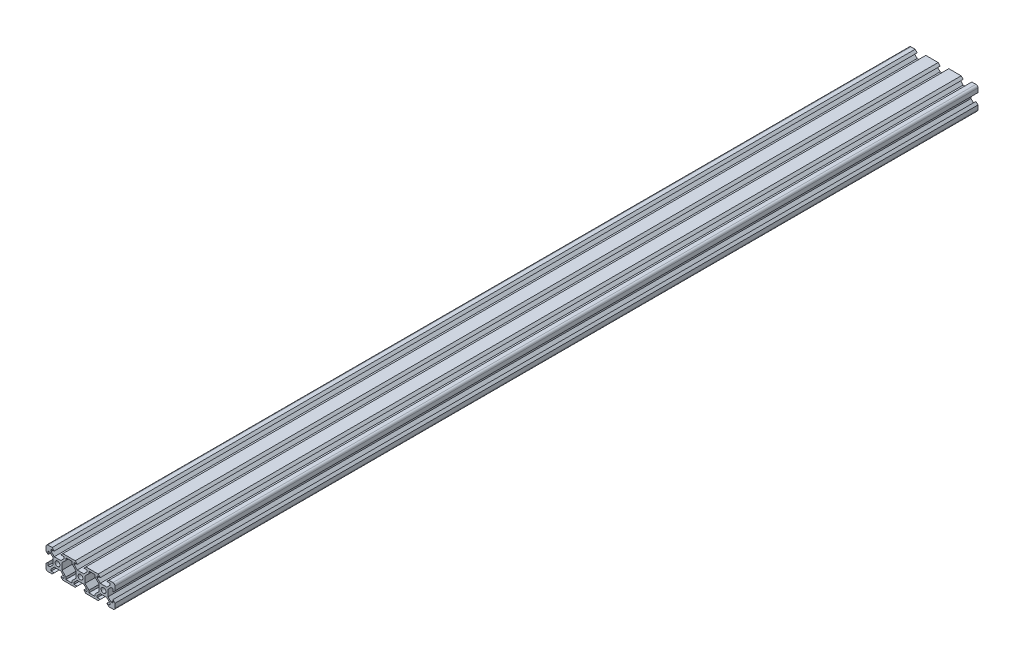
SolidWorks part; units mm, degrees
ref_plane "Front Plane" through (0, 0, 0) normal (0, 0, 1) x (1, 0, 0)
ref_plane "Top Plane" through (0, 0, 0) normal (0, 1, 0) x (1, 0, 0)
ref_plane "Right Plane" through (0, 0, 0) normal (1, 0, 0) x (0, 0, -1)
ref_plane "Plane1" through (0, 0, 10) normal (0, 0, 1) x (1, 0, 0)
sketch "Sketch1" plane through (0, 0, 10) normal (0, 0, 1) x (1, 0, 0)
  line L0 (-13.9007, 2.84) -> (-13.9007, -2.84)
  line L1 (-13.9007, -2.84) -> (-17.3007, -6.24)
  line L2 (-17.3007, -6.24) -> (-17.3007, -8.2)
  line L3 (-17.3007, -8.2) -> (-22.6993, -8.2)
  line L4 (-22.6993, -8.2) -> (-22.6993, -6.24)
  line L5 (-22.6993, -6.24) -> (-26.0993, -2.84)
  line L6 (-26.0993, -2.84) -> (-26.0993, 2.84)
  line L7 (-26.0993, 2.84) -> (-22.6993, 6.24)
  line L8 (-22.6993, 6.24) -> (-22.6993, 8.2)
  line L9 (-22.6993, 8.2) -> (-17.3007, 8.2)
  line L10 (-17.3007, 8.2) -> (-17.3007, 6.24)
  line L11 (-17.3007, 6.24) -> (-13.9007, 2.84)
  line L12 (-6.0993, -2.84) -> (-6.0993, 2.84)
  line L13 (-6.0993, 2.84) -> (-2.6993, 6.24)
  line L14 (-2.6993, 6.24) -> (-2.6993, 8.2)
  line L15 (-2.6993, 8.2) -> (2.6993, 8.2)
  line L16 (2.6993, 8.2) -> (2.6993, 6.24)
  line L17 (2.6993, 6.24) -> (6.0993, 2.84)
  line L18 (6.0993, 2.84) -> (6.0993, -2.84)
  line L19 (6.0993, -2.84) -> (2.6993, -6.24)
  line L20 (2.6993, -6.24) -> (2.6993, -8.2)
  line L21 (2.6993, -8.2) -> (-2.6993, -8.2)
  line L22 (-2.6993, -8.2) -> (-2.6993, -6.24)
  line L23 (-2.6993, -6.24) -> (-6.0993, -2.84)
  line L24 (-12.84, -8.2) -> (-15.4993, -8.2)
  line L25 (-15.4993, -8.2) -> (-15.4993, -6.56)
  line L26 (-15.4993, -6.56) -> (-12.84, -3.9007)
  line L27 (-12.84, -3.9007) -> (-7.16, -3.9007)
  line L28 (-7.16, -3.9007) -> (-4.5007, -6.56)
  line L29 (-4.5007, -6.56) -> (-4.5007, -8.2)
  line L30 (-4.5007, -8.2) -> (-7.16, -8.2)
  line L31 (-7.16, -8.2) -> (-5.36, -10)
  line L32 (-5.36, -10) -> (5.36, -10)
  line L33 (5.36, -10) -> (7.16, -8.2)
  line L34 (7.16, -8.2) -> (4.5007, -8.2)
  line L35 (4.5007, -8.2) -> (4.5007, -6.56)
  line L36 (4.5007, -6.56) -> (7.16, -3.9007)
  line L37 (7.16, -3.9007) -> (12.84, -3.9007)
  line L38 (12.84, -3.9007) -> (15.4993, -6.56)
  line L39 (15.4993, -6.56) -> (15.4993, -8.2)
  line L40 (15.4993, -8.2) -> (12.84, -8.2)
  line L41 (12.84, -8.2) -> (14.64, -10)
  line L42 (14.64, -10) -> (18.2, -10)
  line L43 (20, -8.2) -> (20, -4.64)
  line L44 (20, -4.64) -> (18.2, -2.84)
  line L45 (18.2, -2.84) -> (18.2, -5.4993)
  line L46 (18.2, -5.4993) -> (16.56, -5.4993)
  line L47 (16.56, -5.4993) -> (13.9007, -2.84)
  line L48 (13.9007, -2.84) -> (13.9007, 2.84)
  line L49 (13.9007, 2.84) -> (16.56, 5.4993)
  line L50 (16.56, 5.4993) -> (18.2, 5.4993)
  line L51 (18.2, 5.4993) -> (18.2, 2.84)
  line L52 (18.2, 2.84) -> (20, 4.64)
  line L53 (20, 4.64) -> (20, 8.2)
  line L54 (18.2, 10) -> (14.64, 10)
  line L55 (14.64, 10) -> (12.84, 8.2)
  line L56 (12.84, 8.2) -> (15.4993, 8.2)
  line L57 (15.4993, 8.2) -> (15.4993, 6.56)
  line L58 (15.4993, 6.56) -> (12.84, 3.9007)
  line L59 (12.84, 3.9007) -> (7.16, 3.9007)
  line L60 (7.16, 3.9007) -> (4.5007, 6.56)
  line L61 (4.5007, 6.56) -> (4.5007, 8.2)
  line L62 (4.5007, 8.2) -> (7.16, 8.2)
  line L63 (7.16, 8.2) -> (5.36, 10)
  line L64 (5.36, 10) -> (-5.36, 10)
  line L65 (-5.36, 10) -> (-7.16, 8.2)
  line L66 (-7.16, 8.2) -> (-4.5007, 8.2)
  line L67 (-4.5007, 8.2) -> (-4.5007, 6.56)
  line L68 (-4.5007, 6.56) -> (-7.16, 3.9007)
  line L69 (-7.16, 3.9007) -> (-12.84, 3.9007)
  line L70 (-12.84, 3.9007) -> (-15.4993, 6.56)
  line L71 (-15.4993, 6.56) -> (-15.4993, 8.2)
  line L72 (-15.4993, 8.2) -> (-12.84, 8.2)
  line L73 (-12.84, 8.2) -> (-14.64, 10)
  line L74 (-14.64, 10) -> (-25.36, 10)
  line L75 (-25.36, 10) -> (-27.16, 8.2)
  line L76 (-27.16, 8.2) -> (-24.5007, 8.2)
  line L77 (-24.5007, 8.2) -> (-24.5007, 6.56)
  line L78 (-24.5007, 6.56) -> (-27.16, 3.9007)
  line L79 (-27.16, 3.9007) -> (-32.84, 3.9007)
  line L80 (-32.84, 3.9007) -> (-35.4993, 6.56)
  line L81 (-35.4993, 6.56) -> (-35.4993, 8.2)
  line L82 (-35.4993, 8.2) -> (-32.84, 8.2)
  line L83 (-32.84, 8.2) -> (-34.64, 10)
  line L84 (-34.64, 10) -> (-38.2, 10)
  line L85 (-40, 8.2) -> (-40, 4.64)
  line L86 (-40, 4.64) -> (-38.2, 2.84)
  line L87 (-38.2, 2.84) -> (-38.2, 5.4993)
  line L88 (-38.2, 5.4993) -> (-36.56, 5.4993)
  line L89 (-36.56, 5.4993) -> (-33.9007, 2.84)
  line L90 (-33.9007, 2.84) -> (-33.9007, -2.84)
  line L91 (-33.9007, -2.84) -> (-36.56, -5.4993)
  line L92 (-36.56, -5.4993) -> (-38.2, -5.4993)
  line L93 (-38.2, -5.4993) -> (-38.2, -2.84)
  line L94 (-38.2, -2.84) -> (-40, -4.64)
  line L95 (-40, -4.64) -> (-40, -8.2)
  line L96 (-38.2, -10) -> (-34.64, -10)
  line L97 (-34.64, -10) -> (-32.84, -8.2)
  line L98 (-32.84, -8.2) -> (-35.4993, -8.2)
  line L99 (-35.4993, -8.2) -> (-35.4993, -6.56)
  line L100 (-35.4993, -6.56) -> (-32.84, -3.9007)
  line L101 (-32.84, -3.9007) -> (-27.16, -3.9007)
  line L102 (-27.16, -3.9007) -> (-24.5007, -6.56)
  line L103 (-24.5007, -6.56) -> (-24.5007, -8.2)
  line L104 (-24.5007, -8.2) -> (-27.16, -8.2)
  line L105 (-27.16, -8.2) -> (-25.36, -10)
  line L106 (-25.36, -10) -> (-14.64, -10)
  line L107 (-14.64, -10) -> (-12.84, -8.2)
  circle A0 centre (-10, 0) radius 2.1
  circle A1 centre (-30, 0) radius 2.1
  circle A2 centre (10, 0) radius 2.1
  arc A3 (18.2, -10) -> (20, -8.2) centre (18.2, -8.2) ccw
  arc A4 (20, 8.2) -> (18.2, 10) centre (18.2, 8.2) ccw
  arc A5 (-38.2, 10) -> (-40, 8.2) centre (-38.2, 8.2) ccw
  arc A6 (-40, -8.2) -> (-38.2, -10) centre (-38.2, -8.2) ccw
extrude "Boss-Extrude1" add sketch "Sketch1" against normal up to surface (750 mm away)
